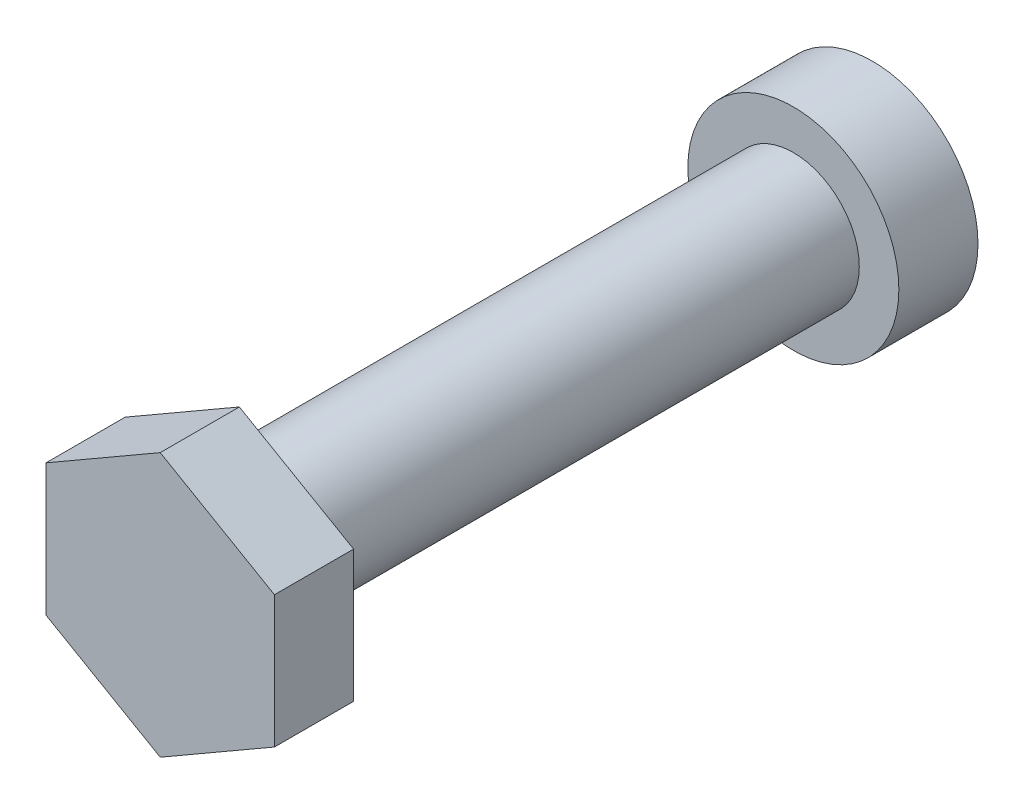
SolidWorks part; units mm, degrees
ref_plane "Front Plane" through (0, 0, 0) normal (0, 0, 1) x (1, 0, 0)
ref_plane "Top Plane" through (0, 0, 0) normal (0, 1, 0) x (1, 0, 0)
ref_plane "Right Plane" through (0, 0, 0) normal (1, 0, 0) x (0, 0, -1)
sketch "Sketch1" plane through (0, 0, 0) normal (0, 0, 1) x (1, 0, 0)
  circle A0 centre (0, 0.3533) radius 2.5
  dimension "D1" = 5
extrude "Boss-Extrude1" add sketch "Sketch1" against normal blind 24
sketch "Sketch2" plane through (0, 0, 0) normal (0, 0, 1) x (1, 0, 0)
  line L1 (4.3301, -2.5) -> (4.3301, 2.5)
  line L2 (4.3301, 2.5) -> (0, 5)
  line L3 (0, 5) -> (-4.3301, 2.5)
  line L4 (-4.3301, 2.5) -> (-4.3301, -2.5)
  line L5 (-4.3301, -2.5) -> (0, -5)
  line L6 (0, -5) -> (4.3301, -2.5)
  circle A0 centre (0, 0) radius 4.3301 construction
  point P1 (0, 0)
  point P10 (0, 0)
  dimension "D1" = 5
extrude "Boss-Extrude2" add sketch "Sketch2" along normal blind 3
sketch "Sketch3" plane through (0, 0, -24) normal (0, 0, -1) x (-1, 0, 0)
  circle A0 centre (0, 0.3533) radius 4
  circle A1 centre (0, 0.3533) radius 2.5 construction
  point P2 (0, 0)
  dimension "D1" = 8
extrude "Boss-Extrude3" add sketch "Sketch3" against normal blind 3 separate body
